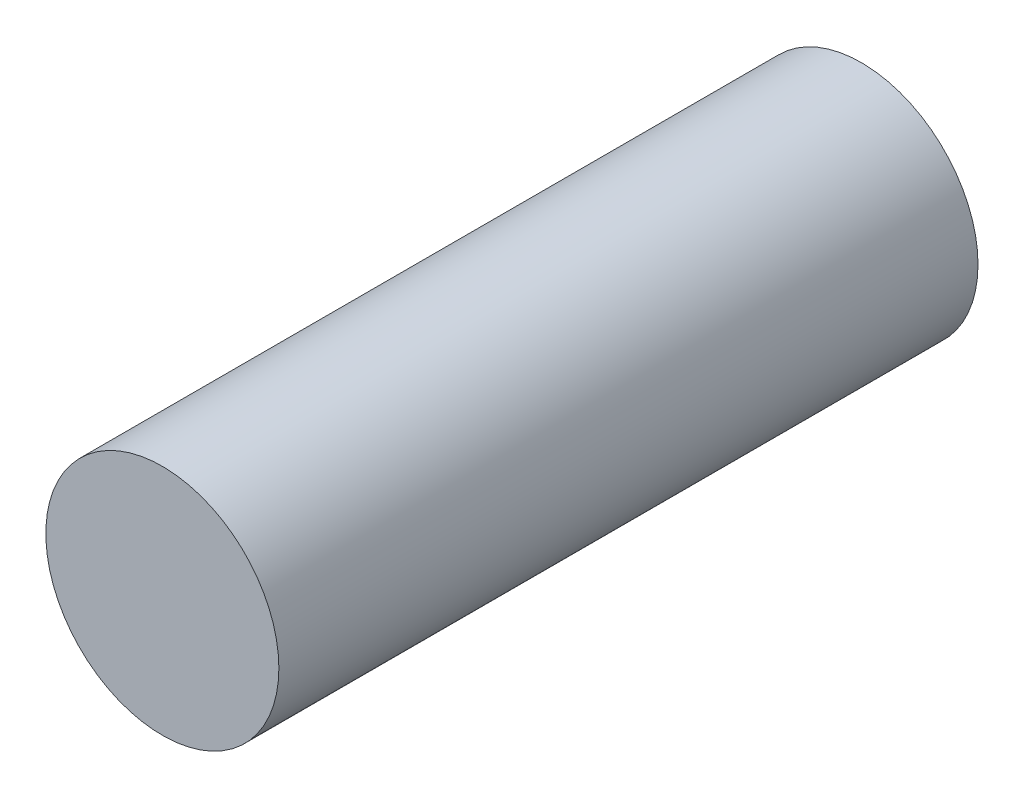
SolidWorks part; units mm, degrees
ref_plane "Front Plane" through (0, 0, 0) normal (0, 0, 1) x (1, 0, 0)
ref_plane "Top Plane" through (0, 0, 0) normal (0, 1, 0) x (1, 0, 0)
ref_plane "Right Plane" through (0, 0, 0) normal (1, 0, 0) x (0, 0, -1)
sketch "Sketch1" plane through (0, 0, 0) normal (0, 0, 1) x (1, 0, 0)
  circle A0 centre (0, 0) radius 5
  dimension "D1" = 10
extrude "Boss-Extrude1" add sketch "Sketch1" along normal mid plane 30
